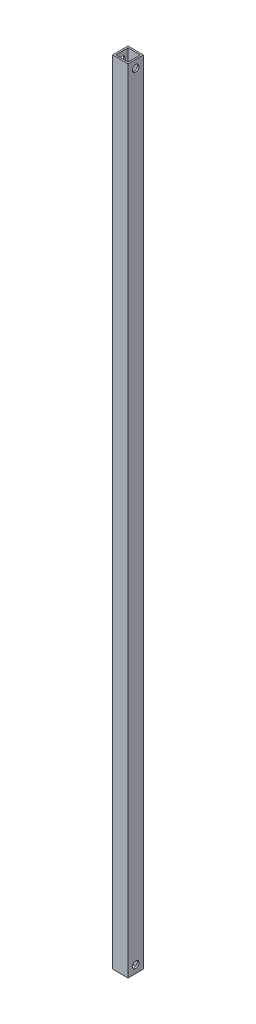
SolidWorks part; units mm, degrees
material "5052-H34"
ref_plane "正面" through (0, 0, 0) normal (0, 0, 1) x (1, 0, 0)
ref_plane "平面" through (0, 0, 0) normal (0, 1, 0) x (1, 0, 0)
ref_plane "右側面" through (0, 0, 0) normal (1, 0, 0) x (0, 0, -1)
sketch "ｽｹｯﾁ1" plane through (0, 0, 0) normal (0, 1, 0) x (1, 0, 0)
  line L1 (-5, 5) -> (5, 5)
  line L2 (-5, 5) -> (-5, -5)
  line L3 (-5, -5) -> (5, -5)
  line L4 (5, 5) -> (5, -5)
  line L5 (-5, 5) -> (5, -5) construction
  line L6 (-5, -5) -> (5, 5) construction
  point P0 (0, 0)
  dimension "D1" = 10
  dimension "D2" = 10
extrude "押し出し-薄板1" add sketch "ｽｹｯﾁ1" along normal blind 513.2159 thin
sketch "ｽｹｯﾁ4" plane through (5, 0, 0) normal (-1, 0, 0) x (0, 0, 1)
  line L0 (5, 256.608) -> (-5, 256.608) construction
  line L2 (-5, 513.2159) -> (5, 513.2159) construction
  line L3 (5, 513.2159) -> (5, 0) construction
  line L4 (-5, 513.2159) -> (-5, 0) construction
  line L5 (0, 0) -> (0, 513.2159) construction
  circle A1 centre (0, 508.2159) radius 2.15
  circle A2 centre (0, 5) radius 2.15
  dimension "D1" = 4.3
  dimension "D2" = 5
extrude "ｶｯﾄ - 押し出し2" cut sketch "ｽｹｯﾁ4" along normal through all
